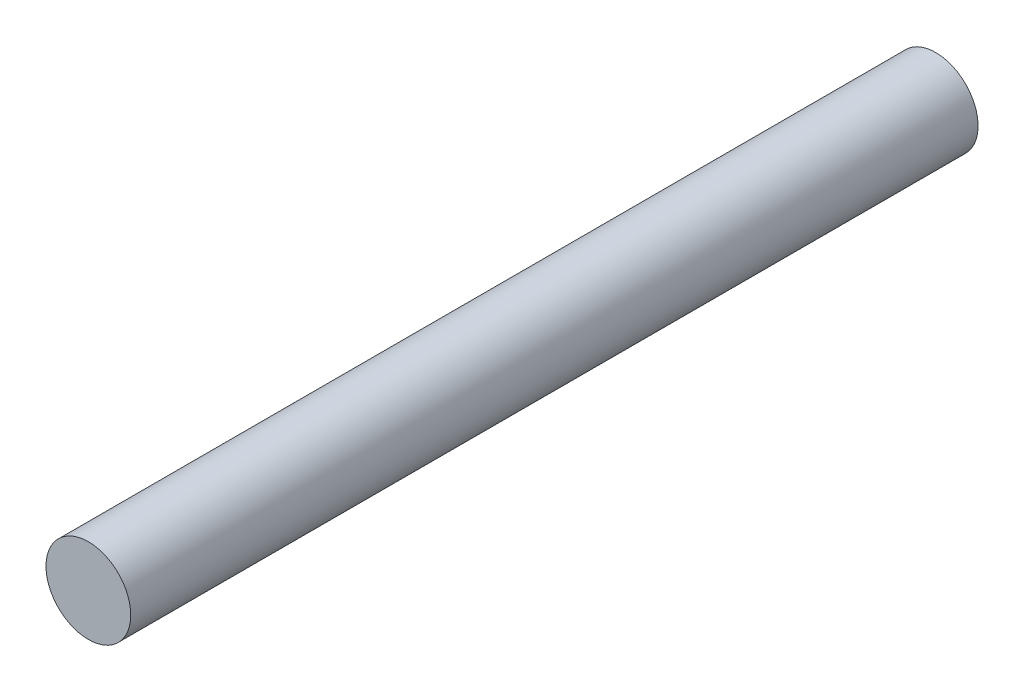
SolidWorks part; units mm, degrees
ref_plane "Front Plane" through (0, 0, 0) normal (0, 0, 1) x (1, 0, 0)
ref_plane "Top Plane" through (0, 0, 0) normal (0, 1, 0) x (1, 0, 0)
ref_plane "Right Plane" through (0, 0, 0) normal (1, 0, 0) x (0, 0, -1)
sketch "Sketch1" plane through (0, 0, 0) normal (0, 0, 1) x (1, 0, 0)
  line L1 (-6.35, 0) -> (6.35, 0) construction
  dimension "OD" = 12.7
sketch "Sketch2" plane through (0, 0, 0) normal (1, 0, 0) x (0, 0, -1)
  line L0 (76.2, 0) -> (-76.2, 0)
  point P0 (-63.5, 0)
  point P3 (63.5, 0)
  point P4 (0, 0)
  dimension "Length" = 152.4
  dimension "D1" = 12.7
  dimension "D2" = 12.7
sketch "Sketch3" plane through (0, 0, 0) normal (0, 0, 1) x (1, 0, 0)
  circle A0 centre (0, 0) radius 6.35
extrude "Boss-Extrude1" add sketch "Sketch3" along normal up to vertex (76.2 mm away) and the other way up to vertex (76.2 mm away) up to point (0, 0, 76.2) other way up to point (0, 0, -76.2)
sketch "Sketch4" plane through (0, 0, -76.2) normal (0, 0, -1) x (-1, 0, 0)
  circle A0 centre (0, 0) radius 6.35 construction
  circle A1 centre (0, 0) radius 6.35
extrude "Cut-Extrude1" cut sketch "Sketch4" against normal blind 25.4
equation "\"D1@Sketch2\"=\"Length@Sketch2\"/12"
equation "\"D2@Sketch2\"=\"Length@Sketch2\"/12"
